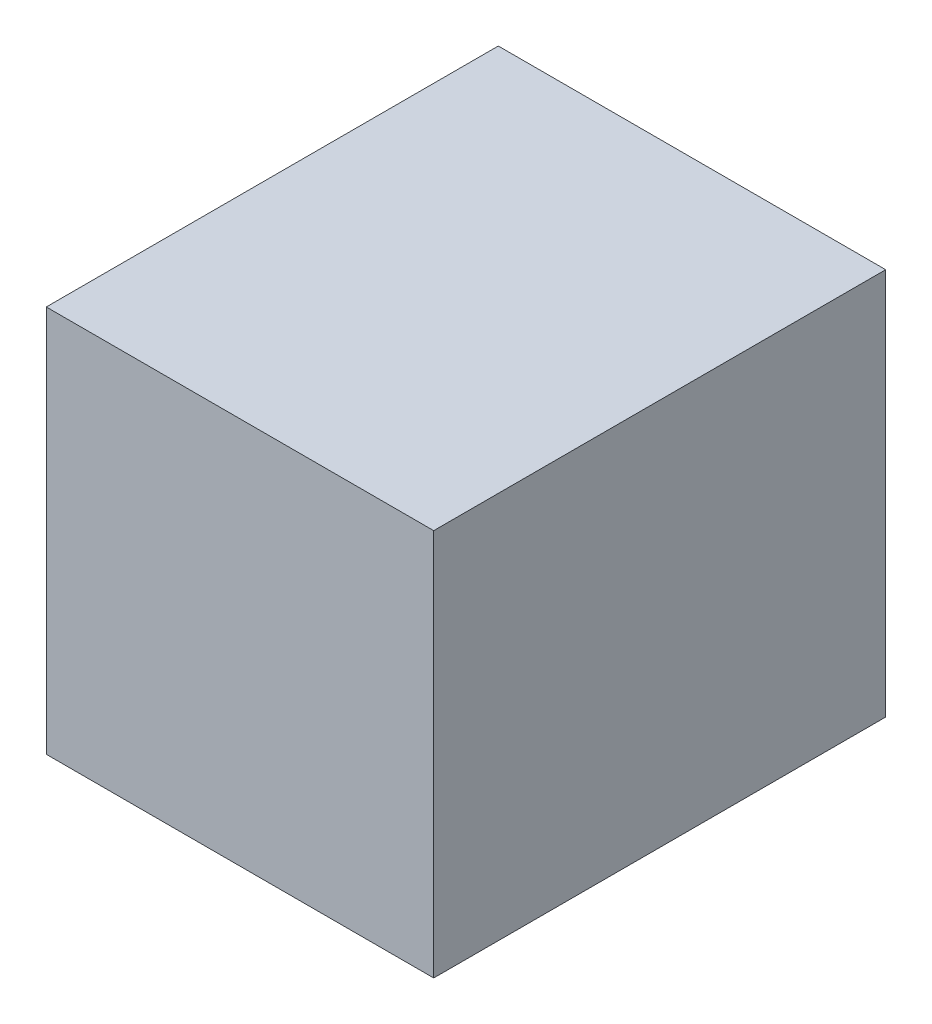
SolidWorks part; units mm, degrees
ref_plane "前视基准面" through (0, 0, 0) normal (0, 0, 1) x (1, 0, 0)
ref_plane "上视基准面" through (0, 0, 0) normal (0, 1, 0) x (1, 0, 0)
ref_plane "右视基准面" through (0, 0, 0) normal (1, 0, 0) x (0, 0, -1)
sketch "草图1" plane through (0, 0, 0) normal (0, 0, 1) x (1, 0, 0)
  line L1 (-30, -30) -> (30, -30)
  line L2 (-30, -30) -> (-30, 30)
  line L3 (-30, 30) -> (30, 30)
  line L4 (30, -30) -> (30, 30)
  line L5 (0, 30) -> (0, -30) construction
  line L6 (-30, 0) -> (30, 0) construction
  point P0 (0, 0)
  dimension "D1" = 60
  dimension "D2" = 60
extrude "凸台-拉伸1" add sketch "草图1" along normal blind 70
